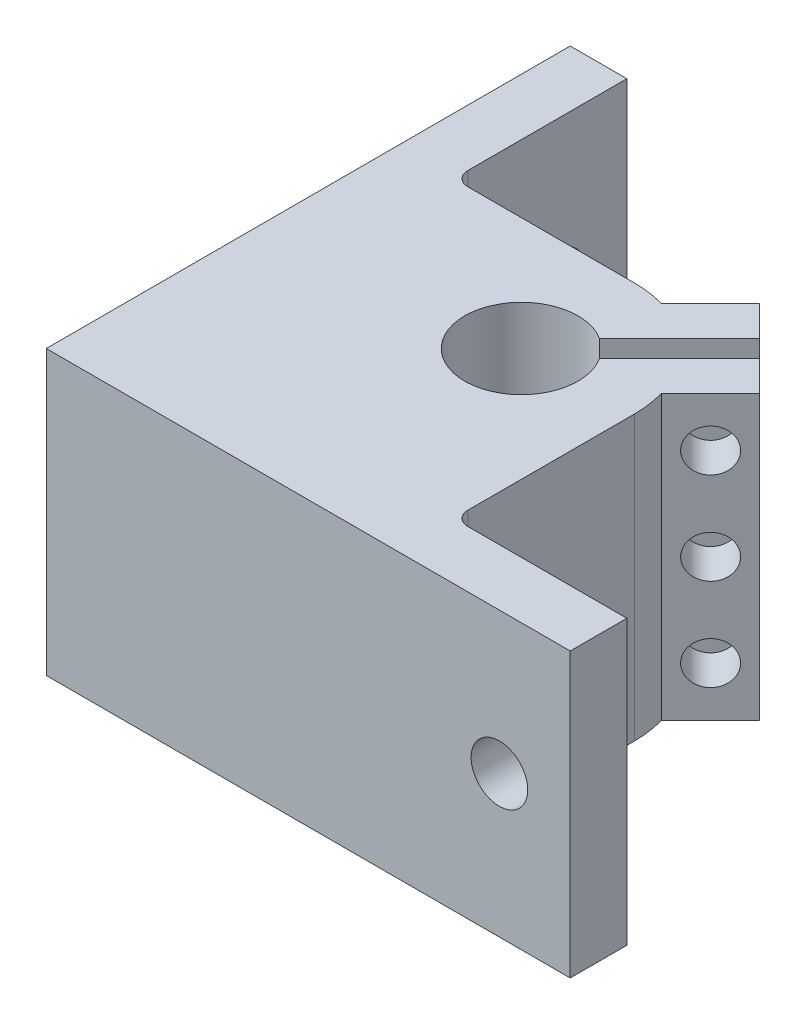
SolidWorks part; units mm, degrees
ref_plane "Front Plane" through (0, 0, 0) normal (0, 0, 1) x (1, 0, 0)
ref_plane "Top Plane" through (0, 0, 0) normal (0, 1, 0) x (1, 0, 0)
ref_plane "Right Plane" through (0, 0, 0) normal (1, 0, 0) x (0, 0, -1)
sketch "Sketch1" plane through (0, 0, 0) normal (0, 1, 0) x (1, 0, 0)
  line L0 (16.775, 24.775) -> (4, 24.775)
  line L1 (0, 0) -> (4, 0)
  line L2 (0, 0) -> (0, 37)
  line L3 (0, 37) -> (4, 37)
  line L4 (4, 0) -> (4, 37)
  line L5 (0, 0) -> (37, 0)
  line L6 (0, 0) -> (0, 4)
  line L7 (0, 4) -> (37, 4)
  line L8 (37, 0) -> (37, 4)
  line L9 (24.775, 16.775) -> (24.775, 4)
  circle A0 centre (16.775, 16.775) radius 4
  circle A1 centre (16.775, 16.775) radius 8
  dimension "D3" = 8
  dimension "D1" = 16.775
  dimension "D2" = 16.775
  dimension "D4" = 4
  dimension "D5" = 4
  dimension "D7" = 37
  dimension "D8" = 37
  dimension "D6" = 4
extrude "Boss-Extrude1" add sketch "Sketch1" along normal blind 20 contours A1 A0 | A1 L0 L4 L7 L9 | L5 L8 L7 L4
fillet "Fillet1" radius 1 2 edges at (4, 10, -24.775) (24.775, 10, -4)
sketch "Sketch2" plane through (0, 0, -4) normal (0, 0, -1) x (-1, 0, 0)
  line L0 (-37, 20) -> (-37, 0) construction
  line L1 (-25.775, 20) -> (-37, 20) construction
  circle A0 centre (-32, 10) radius 2
  dimension "D1" = 4
  dimension "D2" = 5
  dimension "D3" = 10
extrude "Cut-Extrude1" cut sketch "Sketch2" against normal blind 20 contours A0
sketch "Sketch3" plane through (4, 0, 0) normal (1, 0, 0) x (0, 0, -1)
  line L0 (25.775, 20) -> (37, 20) construction
  line L1 (37, 20) -> (37, 0) construction
  circle A0 centre (32, 10) radius 2
  dimension "D1" = 10
  dimension "D2" = 5
  dimension "D3" = 4
extrude "Cut-Extrude2" cut sketch "Sketch3" against normal blind 20
sketch "Sketch7" plane through (0, 20, 0) normal (0, 1, 0) x (1, 0, 0)
  line L1 (20.1536, 18.9162) -> (18.9162, 20.1536)
  line L2 (18.9162, 20.1536) -> (23.1588, 24.3963)
  line L3 (23.1588, 24.3963) -> (24.3963, 23.1588)
  line L4 (24.3963, 23.1588) -> (20.1536, 18.9162)
  line L5 (25.775, 4) -> (37, 4) construction
  circle A0 centre (16.775, 16.775) radius 4 construction
  dimension "D1" = 45
  dimension "D2" = 1.75
  dimension "D3" = 6
extrude "Cut-Extrude4" cut sketch "Sketch7" against normal up to next
sketch "Sketch8" plane through (0, 20, 0) normal (0, 1, 0) x (1, 0, 0)
  line L0 (18.9162, 20.1536) -> (24.5731, 25.8105)
  line L1 (24.5731, 25.8105) -> (22.4517, 27.9318)
  line L2 (22.4517, 27.9318) -> (16.7949, 22.275)
  line L3 (16.7949, 22.275) -> (18.9162, 20.1536)
  line L4 (13.9466, 13.9466) -> (22.4319, 22.4319) construction
  line L5 (25.775, 4) -> (37, 4) construction
  line L6 (22.275, 16.7949) -> (20.1536, 18.9162)
  line L7 (27.9318, 22.4517) -> (22.275, 16.7949)
  line L8 (25.8105, 24.5731) -> (27.9318, 22.4517)
  line L9 (20.1536, 18.9162) -> (25.8105, 24.5731)
  arc A0 (18.9162, 20.1536) -> (20.1536, 18.9162) centre (16.775, 16.775) ccw construction
  arc A1 (24.775, 16.775) -> (23.0166, 21.7792) centre (16.775, 16.775) ccw construction
  dimension "D1" = 45
  dimension "D2" = 3
  dimension "D3" = 8
extrude "Boss-Extrude4" add sketch "Sketch8" against normal up to surface (20 mm away) up to face at (17.1693, 0, -17.1693)
sketch "Sketch9" plane through (2.74, 0, 2.74) normal (0.7071, 0, 0.7071) x (0.7071, 0, -0.7071)
  line L0 (33.1744, 20) -> (33.1744, 0) construction
  line L1 (30.7223, 20) -> (35.6266, 20) construction
  line L2 (35.6266, 0) -> (30.7223, 0) construction
  line L3 (35.6266, 20) -> (33.1744, 16.5) construction
  line L5 (35.6266, 0) -> (33.1744, 3.5) construction
  circle A0 centre (33.1744, 16.5) radius 1.5
  circle A1 centre (33.1744, 10) radius 1.5
  circle A2 centre (33.1744, 3.5) radius 1.5
  dimension "D1" = 3
  dimension "D2" = 3.5
extrude "Cut-Extrude5" cut sketch "Sketch9" against normal through all both and the other way through all
